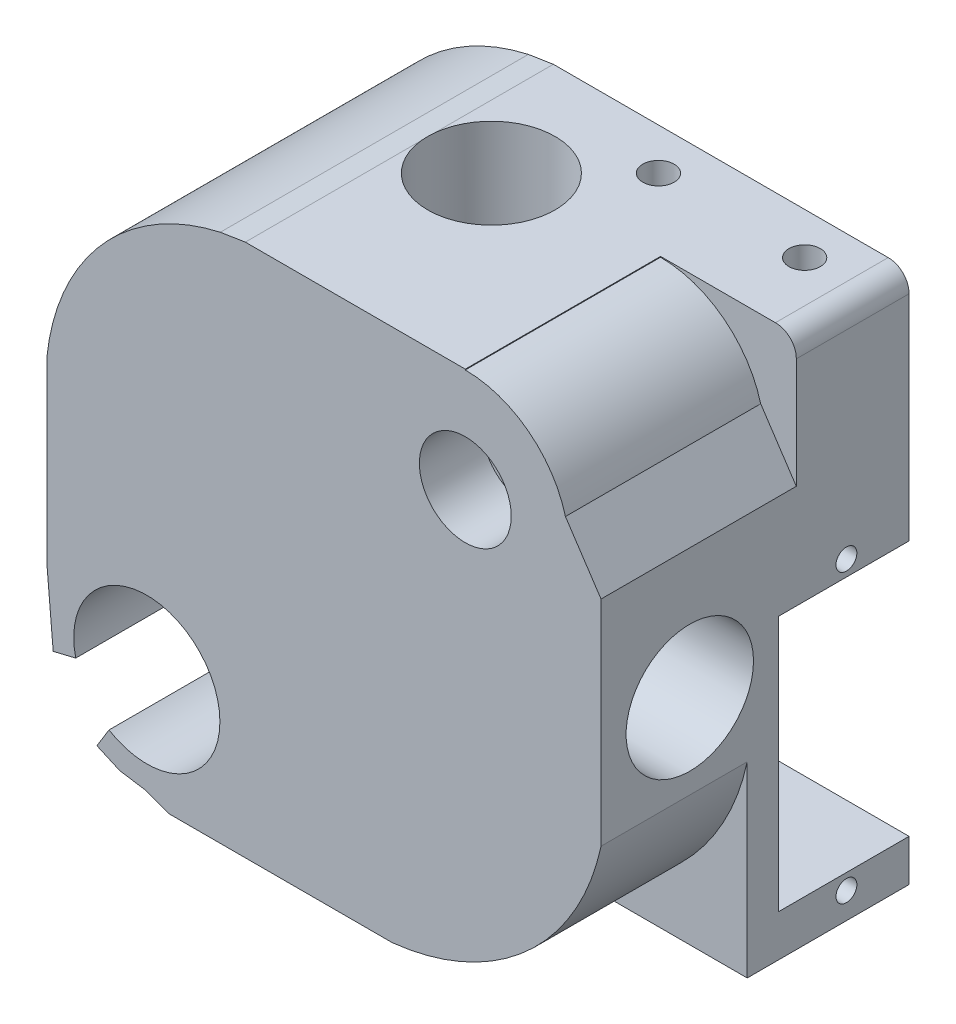
SolidWorks part; units mm, degrees
ref_plane "Alzado" through (0, 0, 0) normal (0, 0, 1) x (1, 0, 0)
ref_plane "Planta" through (0, 0, 0) normal (0, 1, 0) x (1, 0, 0)
ref_plane "Vista lateral" through (0, 0, 0) normal (1, 0, 0) x (0, 0, -1)
sketch "Croquis1" plane through (0, 0, 0) normal (0, 0, 1) x (1, 0, 0)
  line L0 (5.5323, 11.8581) -> (4.9328, 18.779)
  line L1 (4.9328, 18.779) -> (4.9328, 36)
  line L2 (9.721, 6.1246) -> (10.8757, 8.0113)
  line L3 (21.5385, 54.6227) -> (23.9328, 55)
  line L4 (58, 21.9328) -> (58, 53)
  line L6 (5.5323, 11.8581) -> (7.6906, 12.3775)
  line L7 (23.9328, 55) -> (56, 55)
  line L11 (38, 3.9328) -> (16.6419, 3.9328)
  line L12 (16.6419, 3.9328) -> (14.2653, 4.7812)
  line L13 (14.2653, 4.7812) -> (11.9047, 5.1537)
  line L14 (11.9047, 5.1537) -> (9.721, 6.1246)
  arc A0 (21.5385, 54.6227) -> (4.9328, 36) centre (26.2282, 33.726) ccw
  arc A1 (58, 53) -> (56, 55) centre (56.0336, 53.0336) ccw
  arc A2 (38, 3.9328) -> (58, 21.9328) centre (35.5538, 26.7618) ccw
  arc A3 (10.8757, 8.0113) -> (7.6906, 12.3775) centre (14.5, 14) ccw
extrude "Saliente-Extruir1" add sketch "Croquis1" against normal blind 29.5
sketch "Croquis2" plane through (0, 3.9328, 0) normal (0, -1, 0) x (1, 0, 0)
  line L0 (16.6419, -29.5) -> (16.6419, 0) construction
  line L1 (16.6419, 0) -> (38, 0) construction
  circle A0 centre (30, -17.5) radius 6.1
  dimension "D1" = 12.2
  dimension "D2" = 13.3581
  dimension "D3" = 17.5
sketch "Croquis3" plane through (0, 55, 0) normal (0, 1, 0) x (1, 0, 0)
  circle A0 centre (30, 17.5) radius 6.1
  dimension "D1" = 12.2
sketch "Croquis15" plane through (0, 0, 0) normal (0, 0, 1) x (1, 0, 0)
  line L0 (58, 42.4305) -> (58, 53)
  line L1 (45, 55) -> (56, 55)
  line L2 (45, 55) -> (45, 54.9279)
  line L5 (58, 42.4305) -> (54.5896, 47.5695)
  line L6 (58, 21.9328) -> (58, 53) construction
  line L7 (56, 55) -> (23.9328, 55) construction
  arc A0 (54.5896, 47.5695) -> (45, 54.9279) centre (45, 45) ccw
  arc A1 (58, 53) -> (56, 55) centre (56.0336, 53.0336) ccw
  arc A3 (58, 53) -> (56, 55) centre (56.0336, 53.0336) ccw construction
  dimension "D2" = 9.9279
  dimension "D1" = 0.0721
  dimension "D3" = 13
  dimension "D4" = 10
  dimension "D5" = 6.1677
  dimension "D6" = 9.4111
sketch "Croquis4" plane through (4.9328, 0, 0) normal (-1, 0, 0) x (0, 0, 1)
  line L0 (0, 36) -> (0, 18.779) construction
  line L1 (-29.5, 36) -> (0, 36) construction
  circle A0 centre (-8.5, 30) radius 6.1
  dimension "D1" = 12.2
  dimension "D2" = 8.5
  dimension "D3" = 6
sketch "Croquis5" plane through (58, 0, 0) normal (1, 0, 0) x (0, 0, -1)
  circle A0 centre (8.5, 30) radius 6.1
  dimension "D1" = 12.2
sketch "Croquis6" plane through (0, 0, -29.5) normal (0, 0, -1) x (-1, 0, 0)
  line L0 (-4.9328, 36) -> (-4.9328, 18.779) construction
  line L1 (-56, 55) -> (-23.9328, 55) construction
  circle A0 centre (-45, 45) radius 8.5
  dimension "D1" = 17
  dimension "D2" = 40.0672
  dimension "D3" = 10
extrude "Cortar-Extruir11" cut sketch "Croquis15" against normal blind 18.7
sketch "Croquis12" plane through (0, 0, -29.5) normal (0, 0, -1) x (-1, 0, 0)
  line L0 (-4.9328, 36) -> (-4.9328, 18.779) construction
  line L1 (-58, 4) -> (-38, 4)
  line L2 (-58, 4) -> (-58, 32.5)
  line L3 (-58, 32.5) -> (-38, 32.5)
  line L4 (-38, 4) -> (-38, 32.5)
  line L5 (-56, 55) -> (-23.9328, 55) construction
  dimension "D1" = 33.0672
  dimension "D2" = 53.0672
  dimension "D3" = 22.5
  dimension "D4" = 51
extrude "Saliente-Extruir2" add sketch "Croquis12" against normal blind 15.5
extrude "Cortar-Extruir1" cut sketch "Croquis6" against normal blind 10
sketch "Croquis7" plane through (0, 0, -19.5) normal (0, 0, -1) x (-1, 0, 0)
  circle A0 centre (-45, 45) radius 4.1
  circle A1 centre (-45, 45) radius 8.5 construction
  dimension "D1" = 8.2
extrude "Cortar-Extruir2" cut sketch "Croquis7" against normal blind 13.5
sketch "Croquis8" plane through (0, 0, 0) normal (0, 0, 1) x (1, 0, 0)
  line L0 (4.9328, 36) -> (4.9328, 18.779) construction
  line L1 (45, 55) -> (23.9328, 55) construction
  circle A0 centre (45, 45) radius 4.4
  dimension "D1" = 8.8
  dimension "D2" = 40.0672
  dimension "D3" = 10
extrude "Cortar-Extruir3" cut sketch "Croquis8" against normal blind 6
extrude "Cortar-Extruir4" cut sketch "Croquis2" against normal blind 20
extrude "Cortar-Extruir5" cut sketch "Croquis3" against normal blind 20
extrude "Cortar-Extruir6" cut sketch "Croquis4" against normal blind 20
extrude "Cortar-Extruir7" cut sketch "Croquis5" against normal blind 20
sketch "Croquis9" plane through (38, 0, 0) normal (1, 0, 0) x (0, 0, -1)
  circle A0 centre (8.5, 30) radius 3.5
  circle A1 centre (8.5, 30) radius 6.1 construction
  dimension "D1" = 7
extrude "Cortar-Extruir8" cut sketch "Croquis9" against normal up to next
sketch "Croquis10" plane through (0, 23.9328, 0) normal (0, -1, 0) x (1, 0, 0)
  circle A0 centre (30, -17.5) radius 3.5
  circle A1 centre (30, -17.5) radius 6.1 construction
  dimension "D1" = 7
extrude "Cortar-Extruir9" cut sketch "Croquis10" against normal up to next
sketch "Croquis13" plane through (0, 0, -29.5) normal (0, 0, -1) x (-1, 0, 0)
  line L0 (-58, 4) -> (-58, 53) construction
  line L1 (-58, 8) -> (-38, 8)
  line L2 (-58, 8) -> (-58, 32.5)
  line L3 (-58, 32.5) -> (-38, 32.5)
  line L4 (-38, 8) -> (-38, 32.5)
  line L5 (-16.6419, 3.9328) -> (-38, 3.9328) construction
  dimension "D1" = 20
  dimension "D2" = 4.0672
  dimension "D3" = 28.5672
extrude "Cortar-Extruir10" cut sketch "Croquis13" against normal blind 12.5
sketch "Croquis18" plane through (0, 55, 0) normal (0, 1, 0) x (1, 0, 0)
  line L0 (23.9328, 16.8687) -> (23.9328, 0) construction
  line L1 (45, 0) -> (23.9328, 0) construction
  circle A0 centre (38, 25.5) radius 1.5
  circle A1 centre (52, 25.5) radius 1.5
  dimension "D1" = 3
  dimension "D2" = 3
  dimension "D3" = 14.0672
  dimension "D4" = 28.0672
  dimension "D5" = 25.5
extrude "Cortar-Extruir12" cut sketch "Croquis18" against normal up to next
sketch "Croquis19" plane through (58, 0, 0) normal (1, 0, 0) x (0, 0, -1)
  line L0 (29.5, 53) -> (18.7, 53) construction
  line L1 (29.5, 32.5) -> (29.5, 53) construction
  circle A0 centre (23.5, 34) radius 1
  circle A1 centre (23.5, 6.5) radius 1
  dimension "D1" = 2
  dimension "D2" = 2
  dimension "D3" = 6
  dimension "D4" = 19
  dimension "D5" = 46.5
extrude "Cortar-Extruir13" cut sketch "Croquis19" against normal blind 10
sketch "Croquis20" plane through (0, 0, -29.5) normal (0, 0, -1) x (-1, 0, 0)
  line L0 (-58, 4) -> (-58, 8) construction
  line L1 (-16.6419, 3.9328) -> (-38, 3.9328) construction
  circle A0 centre (-16, 36) radius 2.1
  dimension "D1" = 4.2
extrude "Cortar-Extruir14" cut sketch "Croquis20" against normal blind 10
